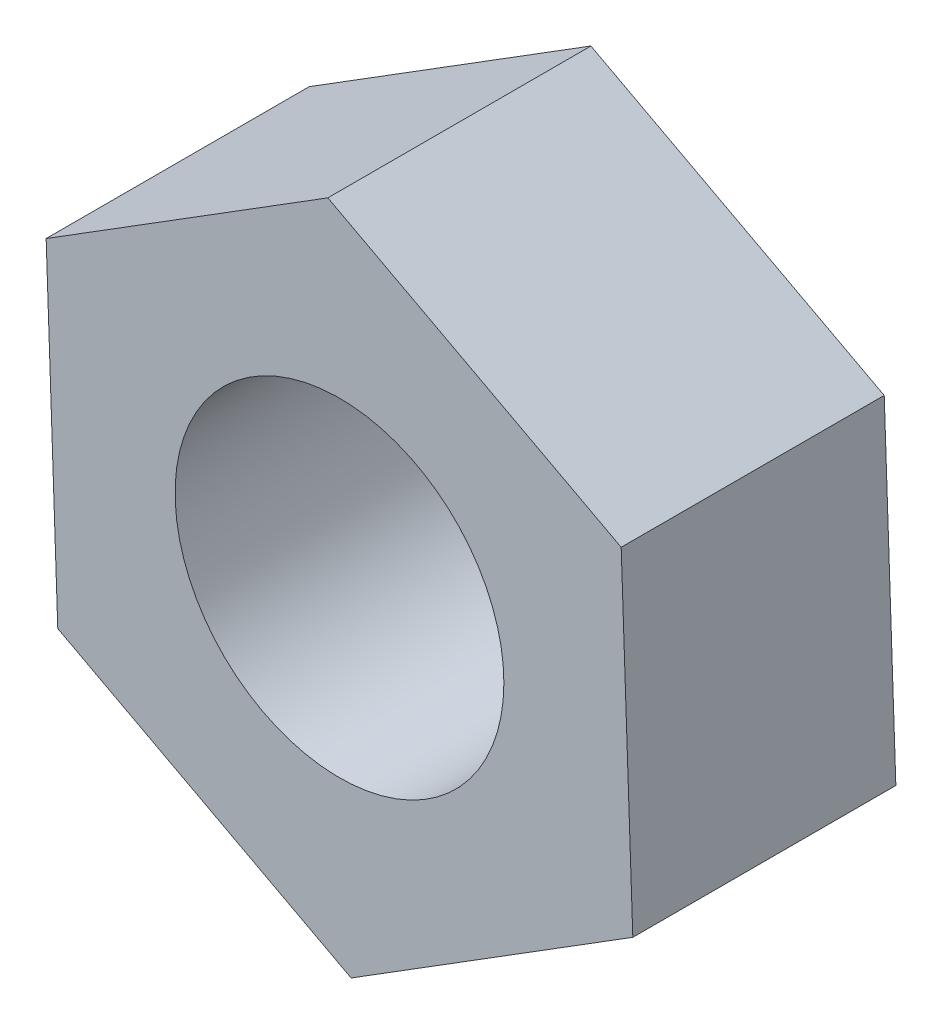
SolidWorks part; units mm, degrees
ref_plane "正面" through (0, 0, 0) normal (0, 0, 1) x (1, 0, 0)
ref_plane "平面" through (0, 0, 0) normal (0, 1, 0) x (1, 0, 0)
ref_plane "右側面" through (0, 0, 0) normal (1, 0, 0) x (0, 0, -1)
sketch "ｽｹｯﾁ1" plane through (0, 0, 0) normal (0, 0, 1) x (1, 0, 0)
  line L1 (3.4271, 2.142) -> (-0.1414, 4.039)
  line L2 (-0.1414, 4.039) -> (-3.5686, 1.897)
  line L3 (-3.5686, 1.897) -> (-3.4271, -2.142)
  line L4 (-3.4271, -2.142) -> (0.1414, -4.039)
  line L5 (0.1414, -4.039) -> (3.5686, -1.897)
  line L6 (3.5686, -1.897) -> (3.4271, 2.142)
  circle A0 centre (0, 0) radius 3.5 construction
  circle A1 centre (0, 0) radius 2
  dimension "D2" = 4
  dimension "D1" = 7
extrude "ﾎﾞｽ - 押し出し1" add sketch "ｽｹｯﾁ1" along normal blind 3.2
cosmetic thread "ねじ山1" parameters "D2"=12
